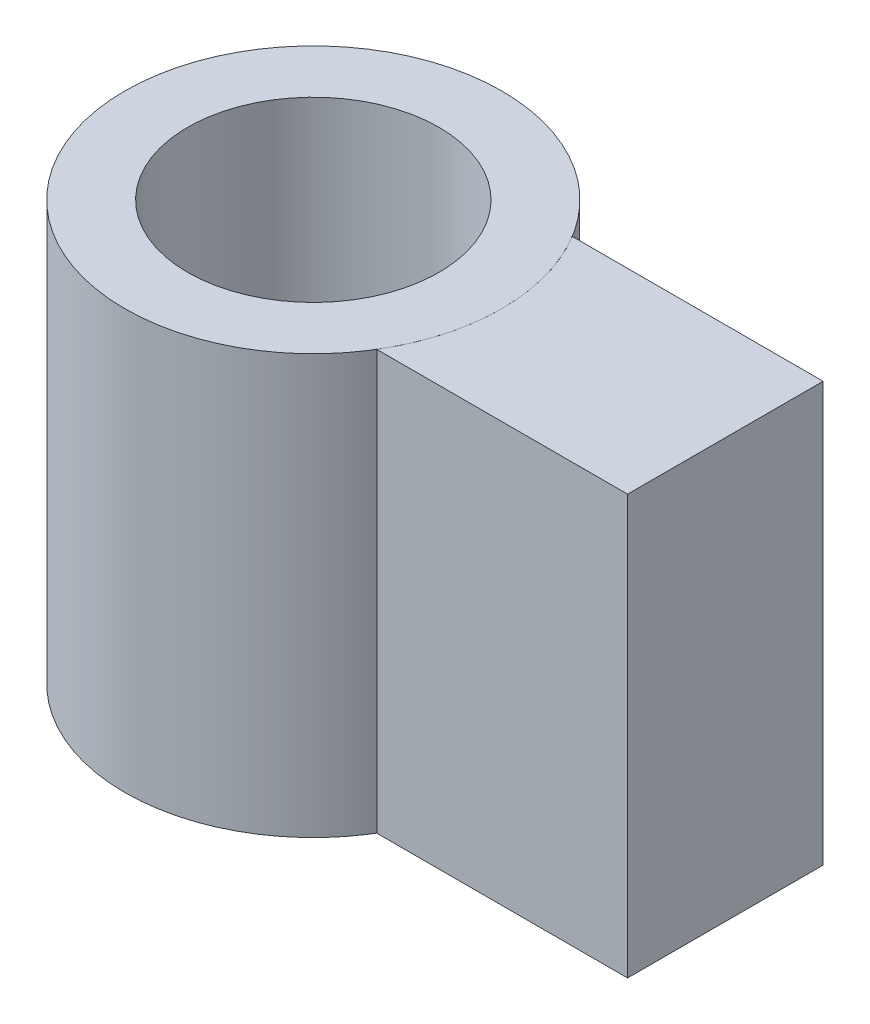
SolidWorks part; units mm, degrees
ref_plane "Front Plane" through (0, 0, 0) normal (0, 0, 1) x (1, 0, 0)
ref_plane "Top Plane" through (0, 0, 0) normal (0, 1, 0) x (1, 0, 0)
ref_plane "Right Plane" through (0, 0, 0) normal (1, 0, 0) x (0, 0, -1)
sketch "Sketch1" plane through (0, 0, 0) normal (0, 1, 0) x (1, 0, 0)
  circle A0 centre (0, 0) radius 13.5
  dimension "D1" = 27
extrude "Boss-Extrude1" add sketch "Sketch1" against normal blind 30
sketch "Sketch2" plane through (0, 0, 0) normal (0, 1, 0) x (1, 0, 0)
  circle A0 centre (0, 0) radius 9
  dimension "D1" = 18
extrude "Cut-Extrude1" cut sketch "Sketch2" against normal through all
ref_plane "Tangent Reference" through (29.5, 0, 0) normal (1, 0, 0) x (0, 0, -1)
sketch "Sketch3" plane through (29.5, 0, 0) normal (1, 0, 0) x (0, 0, -1)
  line L0 (7, 0) -> (7, -30)
  line L1 (13.5, 0) -> (-13.5, 0) construction
  line L2 (-13.5, -30) -> (13.5, -30) construction
  line L3 (-7, 0) -> (-7, -30)
  line L4 (-7, 0) -> (7, 0)
  line L5 (-7, -30) -> (7, -30)
  dimension "D1" = 7
  dimension "D2" = 7
extrude "Boss-Extrude3" add sketch "Sketch3" against normal up to surface (17.9566 mm away) separate body
